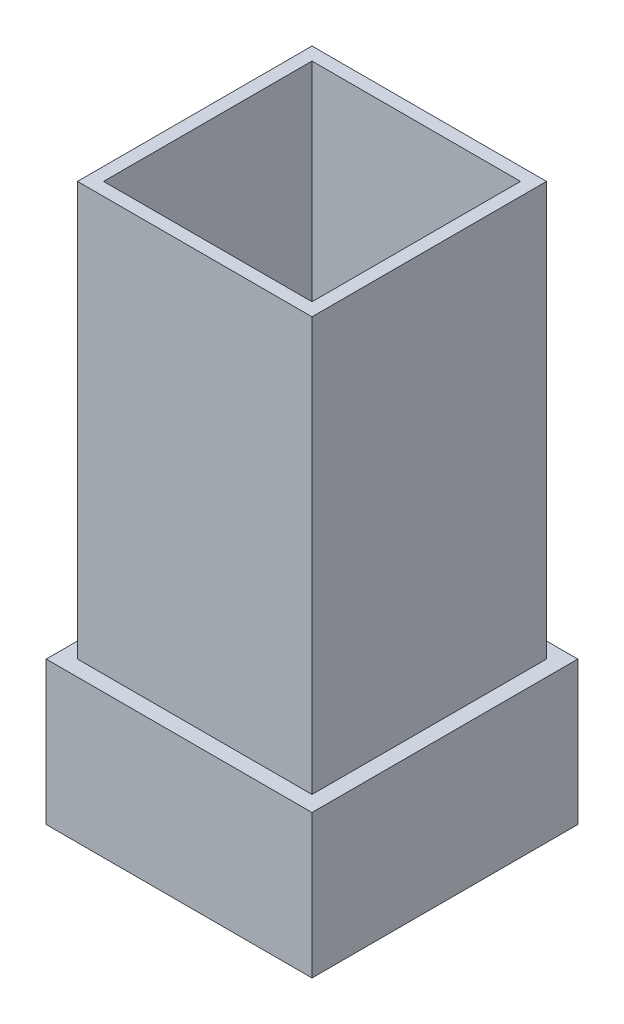
SolidWorks part; units mm, degrees
ref_plane "Front Plane" through (0, 0, 0) normal (0, 0, 1) x (1, 0, 0)
ref_plane "Top Plane" through (0, 0, 0) normal (0, 1, 0) x (1, 0, 0)
ref_plane "Right Plane" through (0, 0, 0) normal (1, 0, 0) x (0, 0, -1)
sketch "Sketch1" plane through (0, 0, 0) normal (0, 1, 0) x (1, 0, 0)
  line L1 (-77.0445, 50.4093) -> (-45.0445, 50.4093)
  line L2 (-77.0445, 50.4093) -> (-77.0445, 18.4093)
  line L3 (-77.0445, 18.4093) -> (-45.0445, 18.4093)
  line L4 (-45.0445, 50.4093) -> (-45.0445, 18.4093)
  line L5 (-81.4445, 54.8093) -> (-40.6445, 54.8093)
  line L6 (-81.4445, 54.8093) -> (-81.4445, 14.0093)
  line L7 (-81.4445, 14.0093) -> (-40.6445, 14.0093)
  line L8 (-40.6445, 54.8093) -> (-40.6445, 14.0093)
  dimension "D1" = 32
  dimension "D2" = 32
  dimension "D3" = 4.4
  dimension "D4" = 4.4
  dimension "D5" = 4.4
  dimension "D6" = 4.4
extrude "Boss-Extrude1" add sketch "Sketch1" along normal blind 10
sketch "Sketch2" plane through (0, 0, 0) normal (0, -1, 0) x (1, 0, 0)
  line L1 (-40.6445, -14.0093) -> (-81.4445, -14.0093)
  line L2 (-40.6445, -14.0093) -> (-40.6445, -54.8093)
  line L3 (-40.6445, -54.8093) -> (-81.4445, -54.8093)
  line L4 (-81.4445, -14.0093) -> (-81.4445, -54.8093)
  line L5 (-75.0445, -20.4093) -> (-47.0445, -20.4093)
  line L6 (-75.0445, -20.4093) -> (-75.0445, -48.4093)
  line L7 (-75.0445, -48.4093) -> (-47.0445, -48.4093)
  line L8 (-47.0445, -20.4093) -> (-47.0445, -48.4093)
  dimension "D1" = 6.4
  dimension "D2" = 6.4
  dimension "D3" = 6.4
  dimension "D4" = 6.4
sketch "Sketch5" plane through (0, 10, 0) normal (0, 1, 0) x (1, 0, 0)
  line L1 (-81.4445, 54.8093) -> (-40.6445, 54.8093)
  line L2 (-81.4445, 54.8093) -> (-81.4445, 14.0093)
  line L3 (-81.4445, 14.0093) -> (-40.6445, 14.0093)
  line L4 (-40.6445, 54.8093) -> (-40.6445, 14.0093)
  line L10 (-77.0445, 50.4093) -> (-77.0445, 18.4093) construction
  line L11 (-43.0445, 16.4093) -> (-79.0445, 16.4093)
  line L12 (-43.0445, 16.4093) -> (-43.0445, 52.4093)
  line L13 (-43.0445, 52.4093) -> (-79.0445, 52.4093)
  line L14 (-79.0445, 16.4093) -> (-79.0445, 52.4093)
  line L15 (-77.0445, 18.4093) -> (-45.0445, 18.4093) construction
  line L16 (-45.0445, 50.4093) -> (-77.0445, 50.4093) construction
  line M5 (-45.0445, 18.4093) -> (-77.0445, 18.4093)
  line M6 (-77.0445, 18.4093) -> (-77.0445, 50.4093)
  line M7 (-77.0445, 50.4093) -> (-45.0445, 50.4093)
  line M8 (-45.0445, 50.4093) -> (-45.0445, 18.4093)
  dimension "D1" = 2
  dimension "D2" = 2
  dimension "D3" = 2
  dimension "D4" = 2
extrude "Boss-Extrude5" add sketch "Sketch5" along normal blind 63.5 contours L14 L11 L12 L13 M8 M5 M6 M7
extrude "Boss-Extrude9" add sketch "Sketch2" along normal blind 2
sketch "Sketch9" plane through (0, -2, 0) normal (0, -1, 0) x (1, 0, 0)
  line L1 (-81.4445, -14.0093) -> (-40.6445, -14.0093)
  line L2 (-81.4445, -14.0093) -> (-81.4445, -54.8093)
  line L3 (-81.4445, -54.8093) -> (-40.6445, -54.8093)
  line L4 (-40.6445, -14.0093) -> (-40.6445, -54.8093)
  line L5 (-79.4445, -16.0093) -> (-42.6445, -16.0093)
  line L6 (-79.4445, -16.0093) -> (-79.4445, -52.8093)
  line L7 (-79.4445, -52.8093) -> (-42.6445, -52.8093)
  line L8 (-42.6445, -16.0093) -> (-42.6445, -52.8093)
  dimension "D1" = 2
  dimension "D2" = 2
  dimension "D3" = 2
  dimension "D4" = 2
extrude "Boss-Extrude11" add sketch "Sketch9" along normal blind 10
equation "\"tolerance\"= 2"
equation "\"length\"= 30"
equation "\"D1@Sketch1\"=\"length\"+\"tolerance\""
equation "\"D2@Sketch1\"=\"length\"+\"tolerance\""
equation "\"protrusion_thickness\" = 4.4"
equation "\"D3@Sketch1\"=\"protrusion_thickness\""
equation "\"D4@Sketch1\"=\"protrusion_thickness\""
equation "\"D5@Sketch1\"=\"protrusion_thickness\""
equation "\"locking protrusion thickness\"=2"
equation "\"D1@Sketch2\"=\"protrusion_thickness\"+\"locking protrusion thickness\""
equation "\"D2@Sketch2\"=\"D1@Sketch2\""
equation "\"D3@Sketch2\"=\"D1@Sketch2\""
equation "\"D4@Sketch2\"=\"D1@Sketch2\""
equation "\"D1@Boss-Extrude1\"=10"
equation "\"D1@Sketch5\"=\"locking protrusion thickness\""
equation "\"D2@Sketch5\"=\"locking protrusion thickness\""
equation "\"D3@Sketch5\"=\"locking protrusion thickness\""
equation "\"D4@Sketch5\"=\"locking protrusion thickness\""
equation "\"D1@Sketch9\"=\"locking protrusion thickness\""
equation "\"D2@Sketch9\"=\"locking protrusion thickness\""
equation "\"D3@Sketch9\"=\"locking protrusion thickness\""
equation "\"D4@Sketch9\"=\"locking protrusion thickness\""
equation "\"D1@Boss-Extrude5\"=2.5*25.4"
